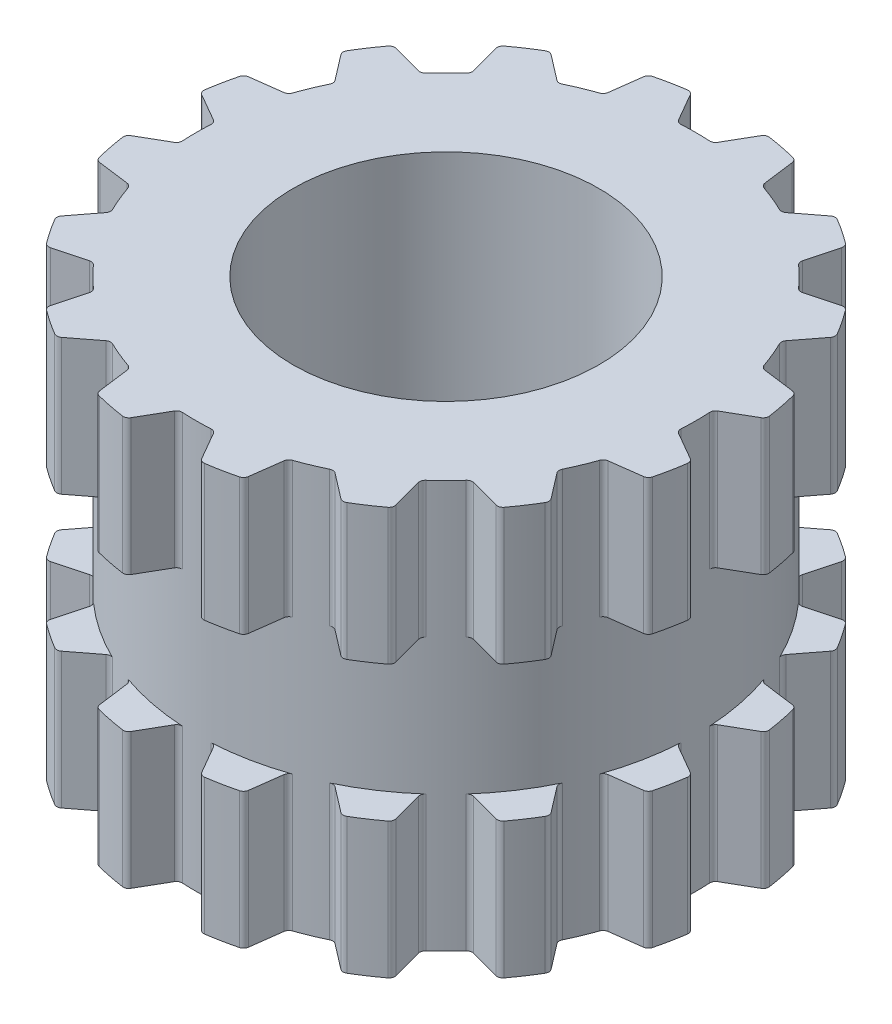
SolidWorks part; units mm, degrees
other "Markup1"
sketch "Sketch5"
material "Brass"
ref_plane "Front Plane" through (0, 0, 0) normal (0, 0, 1) x (1, 0, 0)
ref_plane "Top Plane" through (0, 0, 0) normal (0, 1, 0) x (1, 0, 0)
ref_plane "Right Plane" through (0, 0, 0) normal (1, 0, 0) x (0, 0, -1)
ref_axis "CentralAxis" through (0, 5.5, 0) along (0, -1, 0)
sketch "BodyS" plane through (0, 0, 0) normal (0, 0, 1) x (1, 0, 0)
  line L0 (0, 1.5) -> (2, 1.5)
  line L1 (2, 1.5) -> (2, -1.5)
  line L6 (2, -1.5) -> (0, -1.5)
  line L7 (0, -1.5) -> (0, 1.5) construction
  dimension "Height" = 3
  dimension "ThreadInsertDiameter" = 4
revolve "Body" add sketch "BodyS" angle 360 about L7
hole_wizard "M3x0.5 Tapped Hole1" positions "Sketch2" profile "Sketch3" tap size "M3x0.5" standard "ANSI Metric" end condition through all
sketch "Sketch2" plane through (0, 1.5, 0) normal (0, 1, 0) x (1, 0, 0)
  point P0 (0, 0)
sketch "Sketch3" plane through (0, 1.5, 0) normal (1, 0, 0) x (0, 0, 1)
  line L0 (0, 0) -> (0, 3)
  line L1 (0, 3) -> (1.25, 3)
  line L2 (1.25, 3) -> (1.25, 0)
  line L5 (1.25, 0) -> (0, 0)
  line L11 (0, -6.35) -> (0, 107.95) construction
  dimension "Thru Tap Drill Dia." = 2.5
  dimension "Thru Tap Drill Depth" = 3
cosmetic thread "Hole Thread1" parameters "D2"=3
sketch "MidBodyCutS" plane through (0, 0, 0) normal (0, 0, 1) x (1, 0, 0)
  line L1 (2, 0.5) -> (1.75, 0.5)
  line L2 (2, 0.5) -> (2, -0.5)
  line L3 (2, -0.5) -> (1.75, -0.5)
  line L4 (1.75, 0.5) -> (1.75, -0.5)
  line L5 (2, 0.5) -> (1.75, -0.5) construction
  line L6 (2, -0.5) -> (1.75, 0.5) construction
  line L7 (2, -1.5) -> (2, 1.5) construction
  line L8 (0, 0) -> (1.875, 0) construction
  line L9 (2, 1.5) -> (-2, 1.5) construction
  point P0 (1.875, 0)
  dimension "Width" = 0.25
  dimension "RefHeight" = 1
  dimension "Height" = 1
revolve "MidBodyCut" cut sketch "MidBodyCutS" angle 360 about axis through (0, 5.5, 0) along (0, -1, 0)
sketch "GrooveCutS" plane through (0, 0, 0) normal (0, 1, 0) x (1, 0, 0)
  line L4 (0, 0) -> (0, 1.75) construction
  line L5 (0.1369, 1.7671) -> (0.248, 1.9595)
  line L6 (0, 1.75) -> (0, 2) construction
  line L7 (-0.1369, 1.7671) -> (-0.248, 1.9595)
  circle A0 centre (0, 0) radius 1.75 construction
  circle A1 centre (0, 0) radius 2 construction
  arc A2 (0.0999, 1.7471) -> (-0.0999, 1.7471) centre (0, 0) ccw
  arc A3 (0.2884, 1.9791) -> (-0.2884, 1.9791) centre (0, 0) ccw
  arc A4 (0.248, 1.9595) -> (0.2884, 1.9791) centre (0.2826, 1.9395) cw
  arc A5 (0.1369, 1.7671) -> (0.0999, 1.7471) centre (0.1022, 1.7871) cw
  arc A6 (-0.248, 1.9595) -> (-0.2884, 1.9791) centre (-0.2826, 1.9395) ccw
  arc A7 (-0.1369, 1.7671) -> (-0.0999, 1.7471) centre (-0.1022, 1.7871) ccw
  point P14 (0.1245, 1.7456)
  dimension "RefInnerDiameter" = 3.5
  dimension "InnerRadius" = 0.04
  dimension "OuterRadius" = 0.04
  dimension "Depth" = 0.25
  dimension "Angle" = 60
  dimension "RefOuterWidth" = 0.5768
  dimension "InnerArcWidth" = 0.2
extrude "GrooveCut" cut sketch "GrooveCutS" against normal through all both and the other way through all
pattern_circular "GCCP" count 16 over 360 about axis through (0, 0, 0) along (0, 1, 0) of "GrooveCut"
scale "Scale1" scale about origin uniform scaling no x scale factor 1.4 y scale factor 1.333 z scale factor 1.4
sketch "Sketch4" plane through (0, 1.9995, 0) normal (0, 1, 0) x (1, 0, 0)
  circle A0 centre (0, 0) radius 1.5
  circle A1 centre (0, 0) radius 1.75
extrude "Boss-Extrude1" add sketch "Sketch4" against normal up to surface (3.999 mm away) up to face at (0, -1.9995, 1.75)
scale "Scale2" scale about centroid uniform scaling yes scale factor 0.667
